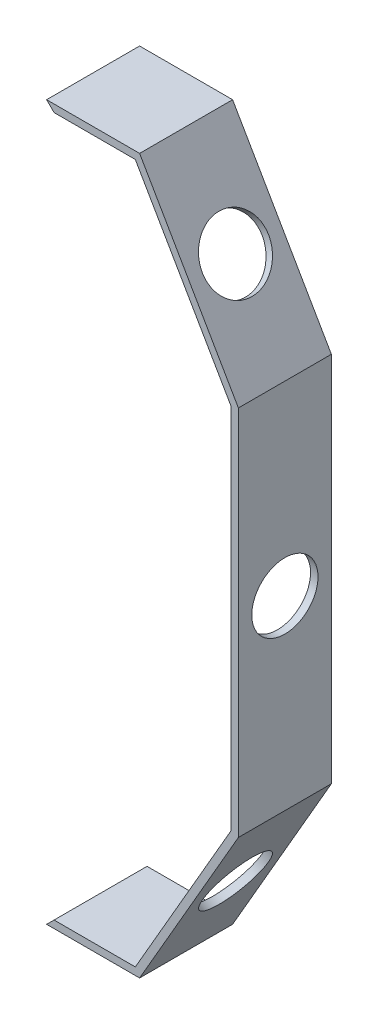
SolidWorks part; units mm, degrees
ref_plane "Alzado" through (0, 0, 0) normal (0, 0, 1) x (1, 0, 0)
ref_plane "Planta" through (0, 0, 0) normal (0, 1, 0) x (1, 0, 0)
ref_plane "Vista lateral" through (0, 0, 0) normal (1, 0, 0) x (0, 0, -1)
sketch "Croquis1" plane through (0, 0, 0) normal (0, 0, 1) x (1, 0, 0)
  line L20 (12.5, 96) -> (39.0581, 50)
  line L21 (-12.5, -96) -> (12.5, -96)
  line L23 (-12.5, 96) -> (12.5, 96)
  line L24 (39.0581, -50) -> (39.0581, 50)
  line L25 (39.0581, -50) -> (12.5, -96)
  line L26 (11.3453, 94) -> (37.0581, 49.4641)
  line L27 (37.0581, -49.4641) -> (37.0581, 49.4641)
  line L28 (37.0581, -49.4641) -> (11.3453, -94)
  line L29 (-10.5, -94) -> (11.3453, -94)
  line L31 (-10.5, 94) -> (11.3453, 94)
  line L32 (-12.5, 96) -> (-10.5, 94)
  line L33 (-10.5, -94) -> (-12.5, -96)
  line L35 (-12.5, -96) -> (-12.5, 96) construction
  line L36 (-10.5, -94) -> (-10.5, 94) construction
  point P2 (39.0581, 0)
  point P18 (0, 96)
  point P19 (0, -96)
  dimension "D1" = 100
  dimension "D3" = 60
  dimension "D4" = 2
  dimension "D5" = 192
  dimension "D6" = 25
extrude "Saliente-Extruir2" add sketch "Croquis1" along normal blind 25
sketch "Croquis3" plane through (39.0581, 0, 0) normal (1, 0, 0) x (0, 0, -1)
  line L0 (-25, 50) -> (0, 50) construction
  circle A0 centre (-12.5, 0) radius 8.9
  point P6 (-12.5, 50)
  dimension "D1" = 17.8
extrude "Cortar-Extruir1" cut sketch "Croquis3" against normal blind 25
sketch "Croquis4" plane through (50.9442, 29.4127, 0) normal (0.866, 0.5, 0) x (0, 0, -1)
  line L0 (-25, 76.8884) -> (0, 76.8884) construction
  line L1 (0, 23.7722) -> (0, 76.8884) construction
  circle A0 centre (-12.5, 50.3303) radius 8.9
  point P5 (-12.5, 76.8884)
  point P8 (0, 50.3303)
  dimension "D1" = 17.8
extrude "Cortar-Extruir2" cut sketch "Croquis4" against normal blind 25
sketch "Croquis5" plane through (50.9442, -29.4127, 0) normal (0.866, -0.5, 0) x (0, 0, -1)
  line L0 (-25, -23.7722) -> (0, -23.7722) construction
  line L1 (0, -76.8884) -> (0, -23.7722) construction
  circle A0 centre (-12.5, -50.3303) radius 8.9
  point P4 (-12.5, -23.7722)
  point P7 (0, -50.3303)
  dimension "D1" = 17.8
extrude "Cortar-Extruir3" cut sketch "Croquis5" against normal blind 25
